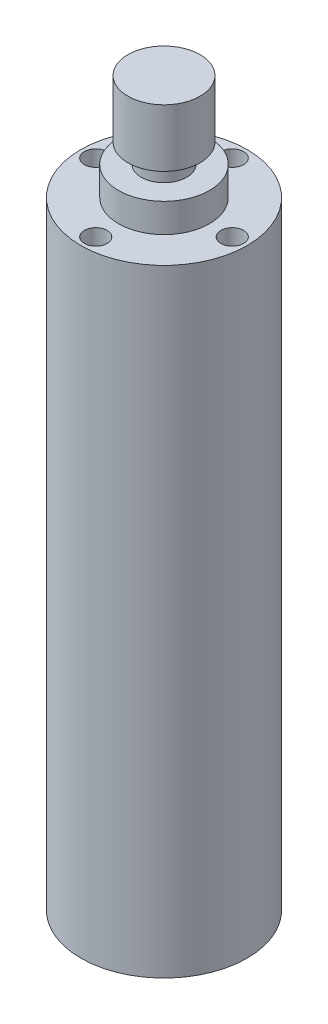
SolidWorks part; units mm, degrees
ref_plane "Front Plane" through (0, 0, 0) normal (0, 0, 1) x (1, 0, 0)
ref_plane "Top Plane" through (0, 0, 0) normal (0, 1, 0) x (1, 0, 0)
ref_plane "Right Plane" through (0, 0, 0) normal (1, 0, 0) x (0, 0, -1)
sketch "Sketch1" plane through (0, 0, 0) normal (0, 1, 0) x (1, 0, 0)
  circle A0 centre (0, 0) radius 10.9855
  dimension "D1" = 21.971
extrude "Boss-Extrude1" add sketch "Sketch1" along normal mid plane 81.534
sketch "Sketch2" plane through (0, 40.767, 0) normal (0, 1, 0) x (1, 0, 0)
  circle A0 centre (0, 0) radius 6.0071
  dimension "D1" = 12.0142
extrude "Boss-Extrude2" add sketch "Sketch2" along normal blind 3.81
sketch "Sketch3" plane through (0, 44.577, 0) normal (0, 1, 0) x (1, 0, 0)
  circle A0 centre (0, 0) radius 2.9972
  dimension "D1" = 5.9944
extrude "Boss-Extrude3" add sketch "Sketch3" along normal blind 2.54
sketch "Sketch4" plane through (0, 47.117, 0) normal (0, 1, 0) x (1, 0, 0)
  circle A0 centre (0, 0) radius 4.7625
  dimension "D1" = 9.525
extrude "Boss-Extrude4" add sketch "Sketch4" along normal blind 7.62
sketch "Sketch5" plane through (0, 40.767, 0) normal (0, 1, 0) x (1, 0, 0)
  circle A0 centre (0, 9.017) radius 1.5
  dimension "D1" = 3
  dimension "D2" = 9.017
extrude "Cut-Extrude1" cut sketch "Sketch5" against normal blind 7.62
pattern_circular "CirPattern1" count 4 over 360 about axis through (0, 0, 0) along (0, 1, 0) of "Cut-Extrude1"
